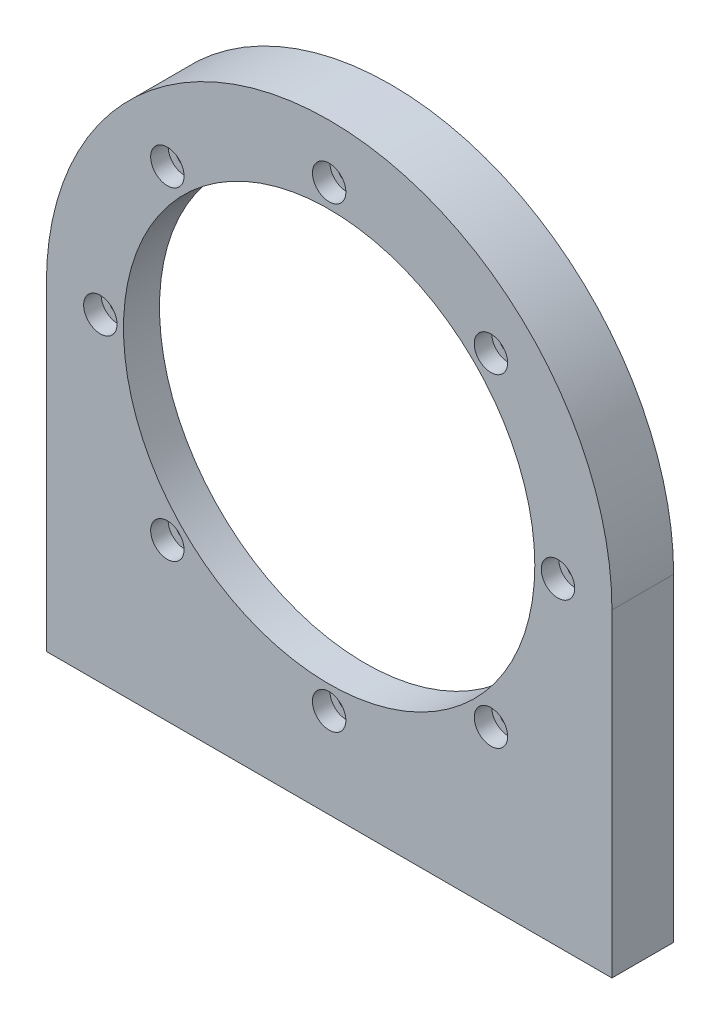
SolidWorks part; units mm, degrees
material "6063-T6"
ref_plane "Front Plane" through (0, 0, 0) normal (0, 0, 1) x (1, 0, 0)
ref_plane "Top Plane" through (0, 0, 0) normal (0, 1, 0) x (1, 0, 0)
ref_plane "Right Plane" through (0, 0, 0) normal (1, 0, 0) x (0, 0, -1)
sketch "Sketch1" plane through (0, 0, 0) normal (0, 0, 1) x (1, 0, 0)
  circle A0 centre (0, 0) radius 55
  circle A1 centre (0, 0) radius 40
  dimension "D1" = 110
  dimension "D2" = 80
extrude "Boss-Extrude1" add sketch "Sketch1" along normal blind 7
sketch "Sketch2" plane through (0, 0, 7) normal (0, 0, 1) x (1, 0, 0)
  circle A0 centre (0, 0) radius 44.5 construction
  point P5 (0, 44.5)
  point P13 (31.4663, 31.4663)
  point P14 (44.5, 0)
  point P15 (31.4663, -31.4663)
  point P16 (0, -44.5)
  point P17 (-31.4663, -31.4663)
  point P18 (-44.5, 0)
  point P19 (-31.4663, 31.4663)
  dimension "D1" = 89
  dimension "D2" = 8
hole_wizard "CBORE for M3 Hex Socket Head Cap Screw1" positions "Sketch2" profile "Sketch3" counterbore size "M3" standard "DIN" end condition through all
sketch "Sketch3" plane through (-31.4663, 31.4663, 7) normal (1, 0, 0) x (0, -1, 0)
  line L0 (0, 0) -> (0, 7)
  line L1 (0, 7) -> (1.7, 7)
  line L3 (1.7, 7) -> (1.7, 3.4)
  line L4 (1.7, 3.4) -> (3.25, 3.4)
  line L5 (3.25, 3.4) -> (3.25, 0)
  line L7 (3.25, 0) -> (0, 0)
  line L11 (0, -6.35) -> (0, 107.95) construction
  dimension "Thru Hole Dia." = 3.4
  dimension "Thru Hole Depth" = 7
  dimension "C'Bore Dia." = 6.5
  dimension "C'Bore Depth" = 3.4
sketch "Sketch4" plane through (0, 0, 0) normal (0, 0, -1) x (-1, 0, 0)
  circle A0 centre (0, 0) radius 50
  circle A1 centre (0, 0) radius 55 construction
  circle A2 centre (0, 0) radius 55
  dimension "D1" = 100
extrude "Boss-Extrude3" add sketch "Sketch4" along normal blind 5
sketch "Sketch5" plane through (0, 0, 7) normal (0, 0, 1) x (1, 0, 0)
  line L0 (-55, 0) -> (-55, -62)
  line L1 (-55, -62) -> (55, -62)
  line L2 (55, -62) -> (55, 0)
  circle A0 centre (0, 0) radius 55 construction
  arc A1 (-55, 0) -> (55, 0) centre (0, 0) ccw
  dimension "D1" = 62
extrude "Boss-Extrude4" add sketch "Sketch5" against normal up to surface (12 mm away) up to face at (-55, 0, -5)
sketch "Sketch7" plane through (0, -62, 0) normal (0, -1, 0) x (-1, 0, 0)
  line L0 (-55, -1) -> (55, -1) construction
  line L1 (-55, 5) -> (-55, -7) construction
  line L2 (55, 5) -> (55, -7) construction
  point P9 (0, -1)
  point P19 (25, -1)
  point P20 (50, -1)
  point P21 (0, -1)
  point P22 (25, -1)
  point P23 (-25, -1)
  point P24 (0, -1)
  point P25 (-25, -1)
  point P26 (-50, -1)
  dimension "D1" = 3
  dimension "D2" = 3
hole_wizard "Tap Drill for M3 Helicoil1" positions "Sketch7" profile "Sketch8" hole size "M3x0.5" standard "BSI"
sketch "Sketch8" plane through (50, -62, 1) normal (1, 0, 0) x (0, 0, -1)
  line L0 (0, 0) -> (0, 10.9464)
  line L1 (0, 10.9464) -> (1.575, 10)
  line L2 (1.575, 10) -> (1.575, 0)
  line L5 (1.575, 0) -> (0, 0)
  line L10 (0, 10.9464) -> (-1.575, 10) construction
  line L11 (0, -6.35) -> (0, 107.95) construction
  dimension "Hole Dia." = 3.15
  dimension "Hole Depth" = 10
  dimension "Drill Angle" = 118
